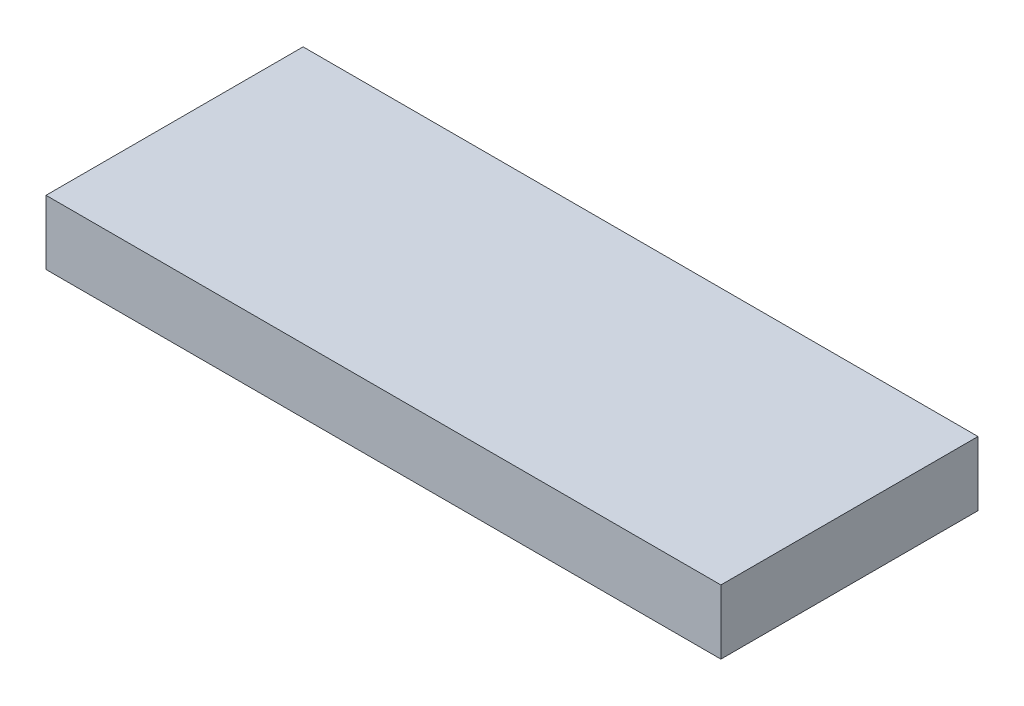
SolidWorks part; units mm, degrees
material "6061 Alloy"
ref_plane "Front Plane" through (0, 0, 0) normal (0, 0, 1) x (1, 0, 0)
ref_plane "Top Plane" through (0, 0, 0) normal (0, 1, 0) x (1, 0, 0)
ref_plane "Right Plane" through (0, 0, 0) normal (1, 0, 0) x (0, 0, -1)
sketch "Sketch1" plane through (0, 0, 0) normal (0, 1, 0) x (1, 0, 0)
  line L1 (-66.675, 25.4) -> (66.675, 25.4)
  line L2 (-66.675, 25.4) -> (-66.675, -25.4)
  line L3 (-66.675, -25.4) -> (66.675, -25.4)
  line L4 (66.675, 25.4) -> (66.675, -25.4)
  line L5 (-66.675, 25.4) -> (66.675, -25.4) construction
  line L6 (-66.675, -25.4) -> (66.675, 25.4) construction
  point P0 (0, 0)
extrude "Boss-Extrude1" add sketch "Sketch1" along normal blind 12.7
